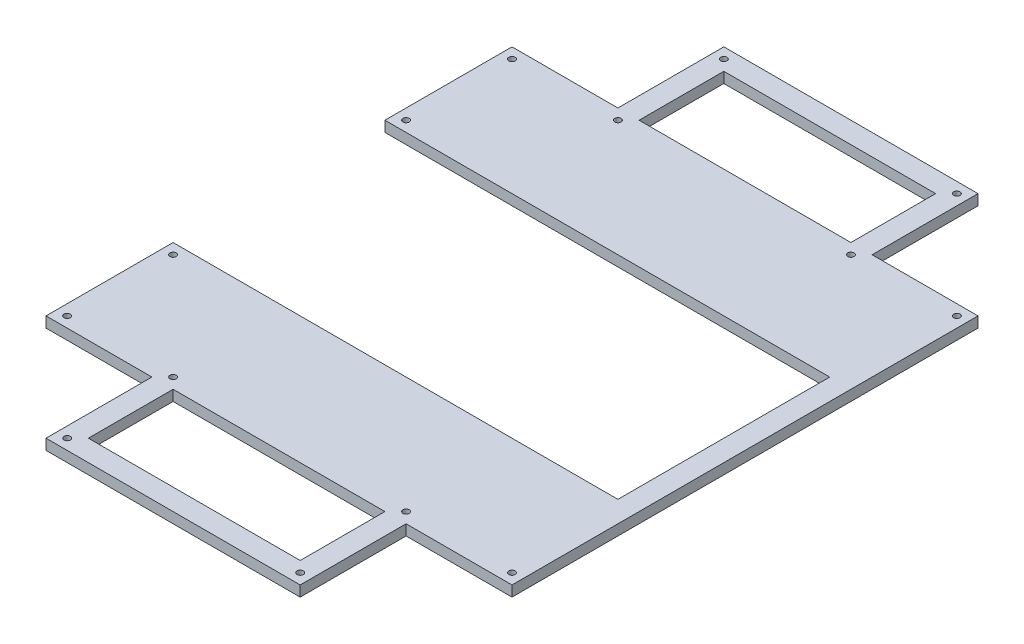
SolidWorks part; units mm, degrees
ref_plane "Plan de face" through (0, 0, 0) normal (0, 0, 1) x (1, 0, 0)
ref_plane "Plan de dessus" through (0, 0, 0) normal (0, 1, 0) x (1, 0, 0)
ref_plane "Plan de droite" through (0, 0, 0) normal (1, 0, 0) x (0, 0, -1)
sketch "Esquisse1" plane through (0, 0, 0) normal (0, 1, 0) x (1, 0, 0)
  line L0 (-60, 110) -> (-60, 160)
  line L1 (110, -110) -> (60, -110)
  line L2 (110, -110) -> (110, 110)
  line L3 (110, 110) -> (60, 110)
  line L4 (-110, -110) -> (-110, -50)
  line L5 (110, -110) -> (-110, 110) construction
  line L6 (110, 110) -> (-110, -110) construction
  line L7 (-60, 160) -> (60, 160)
  line L8 (60, 160) -> (60, 110)
  line L9 (0, 160) -> (0, -89.8749) construction
  line L10 (-108.9276, 0) -> (110, 0) construction
  line L11 (-105, -105) -> (-105, -50) construction
  line L12 (-55, -105) -> (-55, -160) construction
  line L13 (-60, 110) -> (-110, 110)
  line L14 (60, -160) -> (60, -110)
  line L15 (-60, -160) -> (60, -160)
  line L16 (-60, -110) -> (-60, -160)
  line L17 (-60, -110) -> (-110, -110)
  line L18 (50, -150) -> (-50, -150)
  line L19 (50, 110) -> (-50, 110)
  line L20 (50, 110) -> (50, 150)
  line L21 (50, 150) -> (-50, 150)
  line L22 (-50, 110) -> (-50, 150)
  line L23 (50, 110) -> (-50, 150) construction
  line L24 (50, 150) -> (-50, 110) construction
  line L25 (-50, -110) -> (-50, -150)
  line L26 (50, -110) -> (-50, -110)
  line L27 (50, -110) -> (50, -150)
  line L28 (-110, 50) -> (-110, 110)
  line L29 (100, -50) -> (-110, -50)
  line L30 (100, -50) -> (100, 50)
  line L31 (100, 50) -> (-110, 50)
  line L33 (-105, -105) -> (105, -105) construction
  line L34 (105, -105) -> (105, 0) construction
  circle A0 centre (-105, -105) radius 1.5
  circle A1 centre (-105, -55) radius 1.5
  circle A2 centre (-55, -105) radius 1.5
  circle A5 centre (-5, -105) radius 1.5 [skipped]
  circle A6 centre (45, -105) radius 1.5 [skipped]
  circle A7 centre (-55, -155) radius 1.5
  circle A8 centre (-55, 155) radius 1.5
  circle A9 centre (-55, 105) radius 1.5
  circle A10 centre (-105, 105) radius 1.5
  circle A11 centre (-105, 55) radius 1.5
  circle A12 centre (55, -155) radius 1.5
  circle A13 centre (55, -105) radius 1.5
  circle A14 centre (105, -105) radius 1.5
  circle A15 centre (105, 105) radius 1.5
  circle A16 centre (55, 105) radius 1.5
  circle A17 centre (55, 155) radius 1.5
  point P0 (0, 0)
  point P23 (0, 130)
  point P28 (-50, 130)
  point P33 (0.5362, 0)
  dimension "D4" = 3
  dimension "D6" = 50
  dimension "D14" = 5
  dimension "D16" = 5
  dimension "D1" = 220
  dimension "D2" = 50
  dimension "D3" = 50
  dimension "D5" = 5
  dimension "D7" = 30
  dimension "D8" = 10
  dimension "D9" = 10
  dimension "D10" = 10
  dimension "D11" = 60
  dimension "D13" = 2
  dimension "D12" = 60
  dimension "D18" = 120
  dimension "D15" = 4
  dimension "D17" = 2
extrude "Boss.-Extru.1" add sketch "Esquisse1" along normal blind 5
